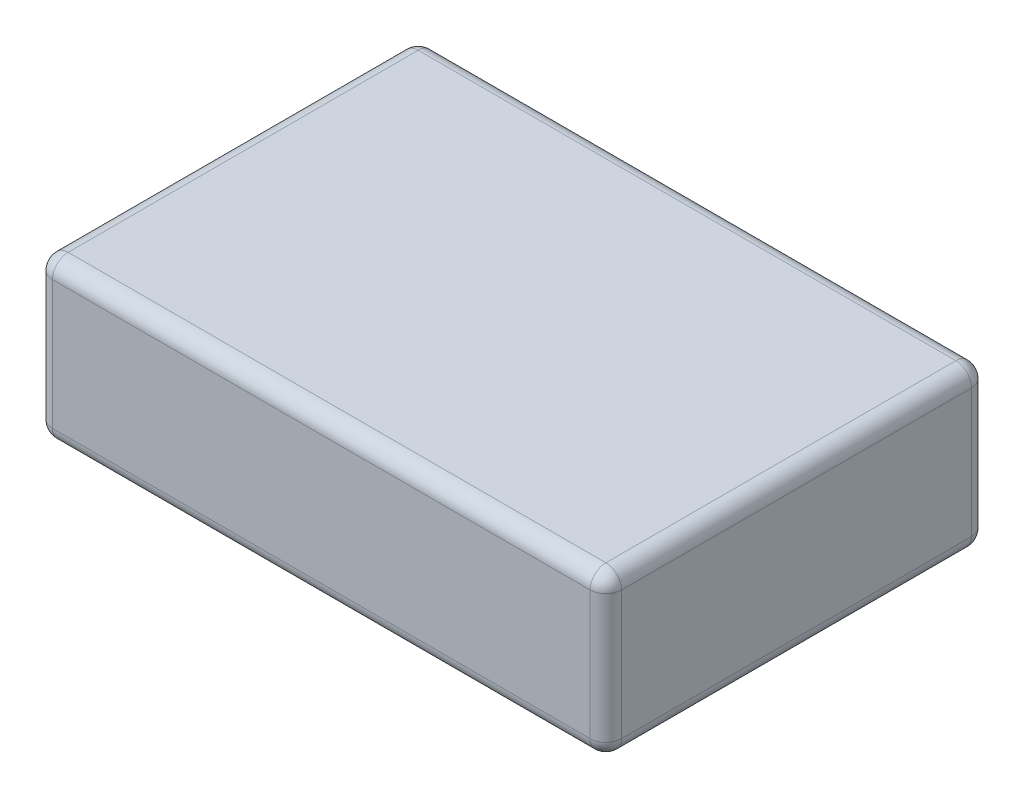
SolidWorks part; units mm, degrees
ref_plane "Front Plane" through (0, 0, 0) normal (0, 0, 1) x (1, 0, 0)
ref_plane "Top Plane" through (0, 0, 0) normal (0, 1, 0) x (1, 0, 0)
ref_plane "Right Plane" through (0, 0, 0) normal (1, 0, 0) x (0, 0, -1)
sketch "Sketch1" plane through (0, 0, 0) normal (0, 1, 0) x (1, 0, 0)
  line L1 (-46.0121, 30.8356) -> (46.0121, 30.8356)
  line L2 (-46.0121, 30.8356) -> (-46.0121, -30.8356)
  line L3 (-46.0121, -30.8356) -> (46.0121, -30.8356)
  line L4 (46.0121, 30.8356) -> (46.0121, -30.8356)
  line L5 (-46.0121, 30.8356) -> (46.0121, -30.8356) construction
  line L6 (-46.0121, -30.8356) -> (46.0121, 30.8356) construction
  point P0 (0, 0)
extrude "Boss-Extrude1" add sketch "Sketch1" along normal blind 25.908
fillet "Fillet1" radius 2.54 12 edges at (-46.0121, 0, 0) (-46.0121, 25.908, 0) (-46.0121, 12.954, -30.8356) (0, 0, -30.8356) (0, 25.908, -30.8356) (46.0121, 12.954, -30.8356) (46.0121, 0, 0) (46.0121, 25.908, 0) (46.0121, 12.954, 30.8356) (0, 0, 30.8356) (-46.0121, 12.954, 30.8356) (0, 25.908, 30.8356)
